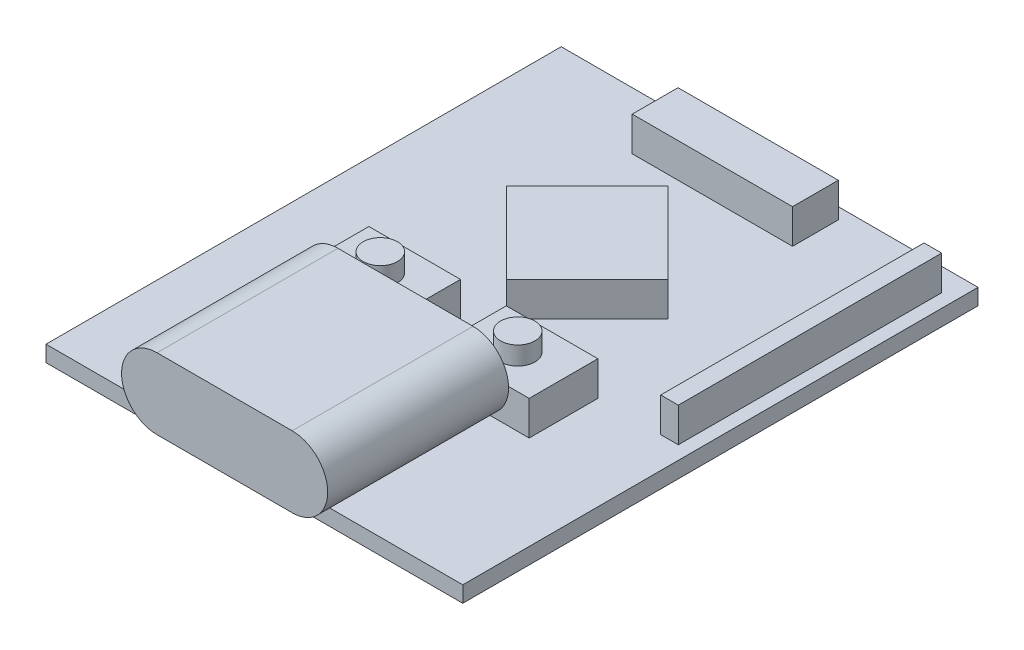
SolidWorks part; units mm, degrees
ref_plane "Спереди" through (0, 0, 0) normal (0, 0, 1) x (1, 0, 0)
ref_plane "Сверху" through (0, 0, 0) normal (0, 1, 0) x (1, 0, 0)
ref_plane "Справа" through (0, 0, 0) normal (1, 0, 0) x (0, 0, -1)
sketch "Эскиз1" plane through (0, 0, 0) normal (0, 1, 0) x (1, 0, 0)
  line L0 (0, 22.5) -> (0, 0) construction
  line L1 (-9.1, 0) -> (9.1, 0)
  line L2 (-9.1, 0) -> (-9.1, 22.5)
  line L3 (-9.1, 22.5) -> (9.1, 22.5)
  line L4 (9.1, 0) -> (9.1, 22.5)
  point P6 (0, -3)
  dimension "D1" = 18.2
  dimension "D2" = 22.5
  dimension "D3" = 3
extrude "Бобышка-Вытянуть1" add sketch "Эскиз1" along normal blind 0.7
sketch "Эскиз2" plane through (0, 0, 0) normal (0, 0, 1) x (1, 0, 0)
  line L0 (-2.95, 2.55) -> (2.95, 2.55) construction
  line L1 (-2.95, 4.1) -> (2.95, 4.1)
  line L2 (-2.95, 1) -> (2.95, 1)
  line L3 (0, 2.55) -> (0, 0) construction
  line L4 (-9.1, 0) -> (9.1, 0) construction
  line L5 (-4.5, 2.55) -> (4.5, 2.55) construction
  arc A0 (-2.95, 4.1) -> (-2.95, 1) centre (-2.95, 2.55) ccw
  arc A1 (2.95, 1) -> (2.95, 4.1) centre (2.95, 2.55) ccw
  point P2 (0, 2.55)
  point P11 (0, 1)
  point P12 (4.5, 2.55)
  point P15 (-4.5, 2.55)
  dimension "D1" = 3.1
  dimension "D2" = 9
  dimension "D3" = 4.1
extrude "Бобышка-Вытянуть2" add sketch "Эскиз2" against normal blind 7.9 from offset 1.3
sketch "Эскиз3" plane through (0, 0, 0) normal (0, 1, 0) x (1, 0, 0)
  line L0 (0, 18.0711) -> (0, 11) construction
  line L1 (-3.5355, 14.5355) -> (0, 18.0711)
  line L2 (-3.5355, 14.5355) -> (0, 11)
  line L3 (0, 11) -> (3.5355, 14.5355)
  line L4 (0, 18.0711) -> (3.5355, 14.5355)
  line L5 (-1, 10) -> (-1, 7)
  line L6 (1, 10) -> (5, 10)
  line L7 (1, 10) -> (1, 7)
  line L8 (1, 7) -> (5, 7)
  line L9 (5, 10) -> (5, 7)
  line L10 (-5, 10) -> (-5, 7)
  line L11 (-1, 7) -> (-5, 7)
  line L12 (-1, 10) -> (-5, 10)
  line L13 (9.1, 22.5) -> (-9.1, 22.5) construction
  line L14 (-3.5, 22) -> (3.5, 22)
  line L15 (-3.5, 22) -> (-3.5, 20)
  line L16 (-3.5, 20) -> (3.5, 20)
  line L17 (3.5, 22) -> (3.5, 20)
  line L18 (-9.1, 0) -> (9.1, 0) construction
  line L19 (7.7438, 21.5) -> (8.5119, 21.5)
  line L20 (7.7438, 21.5) -> (7.7438, 10)
  line L21 (7.7438, 10) -> (8.5119, 10)
  line L22 (8.5119, 21.5) -> (8.5119, 10)
  point P20 (0, 20)
  point P24 (9, 21.5)
  dimension "D1" = 10
  dimension "D2" = 4
  dimension "D3" = 3
  dimension "D4" = 10
  dimension "D5" = 5
  dimension "D6" = 7
  dimension "D7" = 0.5
  dimension "D8" = 2
  dimension "D9" = 11.5
extrude "Бобышка-Вытянуть3" add sketch "Эскиз3" along normal blind 2.2
ref_plane "Плоскость1" through (0, 0, 3) normal (0, 0, 1) x (1, 0, 0)
sketch "Эскиз4" plane through (0, 0, 0) normal (0, 1, 0) x (1, 0, 0)
  line L0 (3, 10) -> (3, 7) construction
  line L1 (5, 10) -> (1, 10) construction
  line L2 (1, 7) -> (5, 7) construction
  line L3 (-3, 10) -> (-3, 7) construction
  line L4 (-1, 10) -> (-5, 10) construction
  line L5 (-5, 7) -> (-1, 7) construction
  line L6 (0, -50) -> (0, 50) construction
  circle A0 centre (3, 8.5) radius 0.75
  circle A1 centre (-3, 8.5) radius 0.75
  dimension "D1" = 1.5
extrude "Бобышка-Вытянуть4" add sketch "Эскиз4" along normal blind 3
